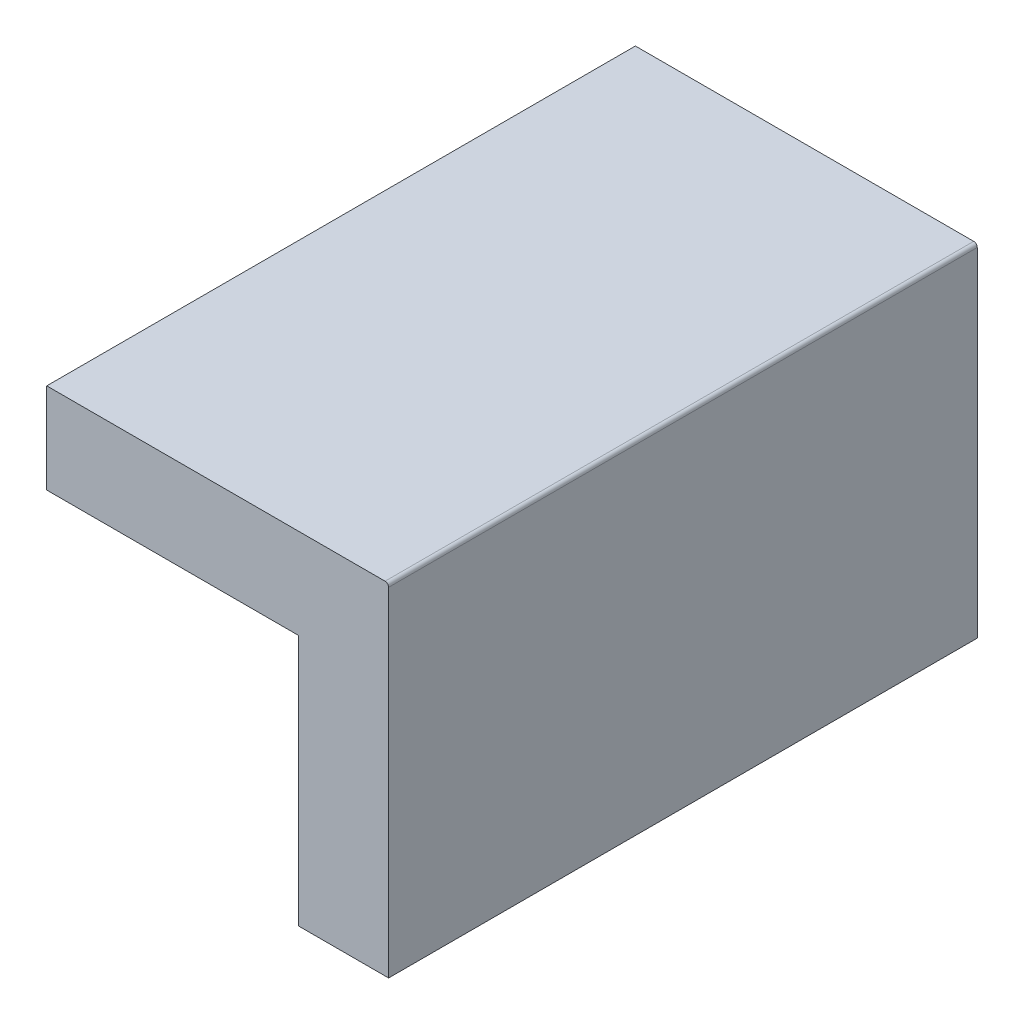
SolidWorks part; units mm, degrees
ref_plane "Front Plane" through (0, 0, 0) normal (0, 0, 1) x (1, 0, 0)
ref_plane "Top Plane" through (0, 0, 0) normal (0, 1, 0) x (1, 0, 0)
ref_plane "Right Plane" through (0, 0, 0) normal (1, 0, 0) x (0, 0, -1)
sketch "Sketch1" plane through (0, 0, 0) normal (0, 0, 1) x (1, 0, 0)
  line L0 (0, -200) -> (0, 0) construction
  line L1 (0, 0) -> (-100, 0) construction
  line L2 (-9.525, 0) -> (-923.925, 0)
  line L3 (0, -9.525) -> (0, -923.925)
  line L4 (-923.925, 0) -> (-923.925, -243.9381)
  line L5 (-923.925, -243.9381) -> (-243.9381, -243.9381)
  line L6 (-243.9381, -243.9381) -> (-243.9381, -923.925)
  line L7 (-243.9381, -923.925) -> (0, -923.925)
  arc A0 (0, -9.525) -> (-9.525, 0) centre (-9.525, -9.525) ccw
  dimension "D1" = 19.05
  dimension "D2" = 914.4
  dimension "D3" = 914.4
  dimension "D4" = 243.9381
extrude "Boss-Extrude2" add sketch "Sketch1" against normal blind 1286.002 and the other way blind 304.8 contours L3 A0 L2 L4 L5 L6 L7
